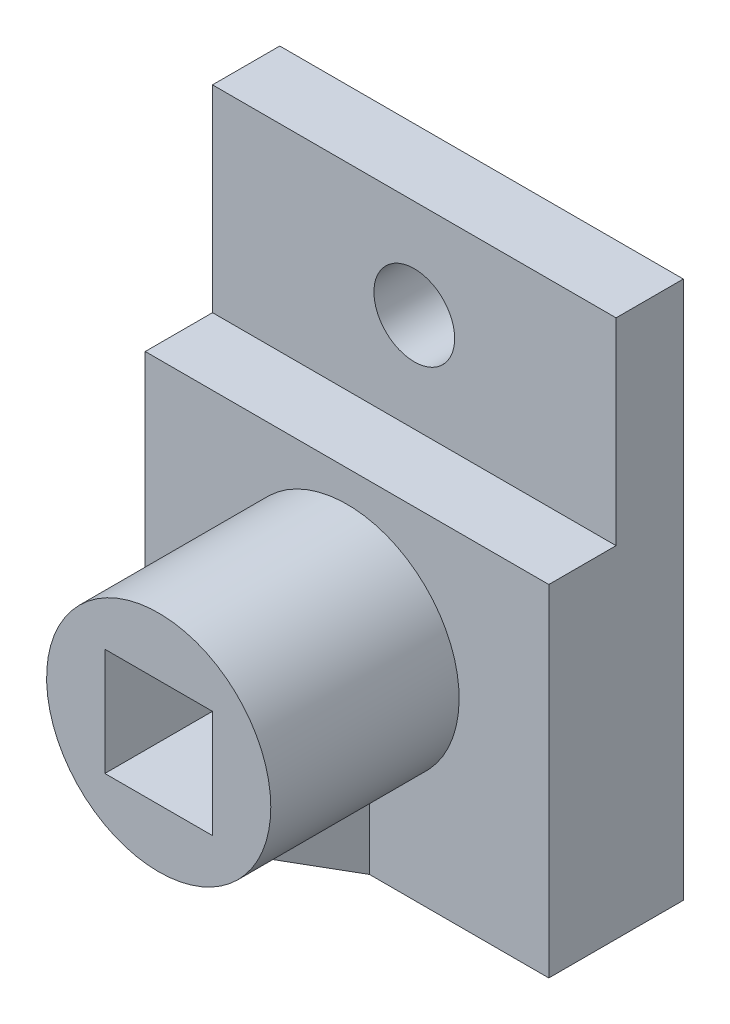
SolidWorks part; units mm, degrees
ref_plane "Спереди" through (0, 0, 0) normal (0, 0, 1) x (1, 0, 0)
ref_plane "Сверху" through (0, 0, 0) normal (0, 1, 0) x (1, 0, 0)
ref_plane "Справа" through (0, 0, 0) normal (1, 0, 0) x (0, 0, -1)
sketch "Эскиз1" plane through (0, 0, 0) normal (0, 0, 1) x (1, 0, 0)
  line L1 (-22.5, -30) -> (22.5, -30)
  line L2 (-22.5, -30) -> (-22.5, 30)
  line L3 (-22.5, 30) -> (22.5, 30)
  line L4 (22.5, -30) -> (22.5, 30)
  line L5 (-22.5, -30) -> (22.5, 30) construction
  line L6 (-22.5, 30) -> (22.5, -30) construction
  point P0 (0, 0)
  dimension "D1" = 45
  dimension "D2" = 60
extrude "Бобышка-Вытянуть1" add sketch "Эскиз1" along normal blind 15
sketch "Эскиз2" plane through (22.5, 0, 0) normal (1, 0, 0) x (0, 0, -1)
  line L0 (-15, 30) -> (0, 30) construction
  line L1 (-15, 30) -> (-7.5, 30)
  line L2 (-15, 30) -> (-15, 8)
  line L3 (-15, 8) -> (-7.5, 8)
  line L4 (-7.5, 30) -> (-7.5, 8)
  dimension "D1" = 22
extrude "Вырез-Вытянуть1" cut sketch "Эскиз2" against normal through all
sketch "Эскиз3" plane through (0, 0, 15) normal (0, 0, 1) x (1, 0, 0)
  line L0 (0, 8) -> (0, -30) construction
  line L1 (-22.5, 8) -> (22.5, 8) construction
  line L2 (-22.5, -30) -> (22.5, -30) construction
  circle A0 centre (0, -8) radius 12.5
  dimension "D1" = 25
  dimension "D2" = 16
extrude "Бобышка-Вытянуть2" add sketch "Эскиз3" along normal blind 21
sketch "Эскиз6" plane through (0, 0, 7.5) normal (0, 0, 1) x (1, 0, 0)
  line L0 (0, 30) -> (0, 8) construction
  line L1 (-22.5, 30) -> (22.5, 30) construction
  line L2 (-22.5, 8) -> (22.5, 8) construction
  circle A0 centre (0, 19) radius 4.5
  dimension "D1" = 9
extrude "Вырез-Вытянуть4" cut sketch "Эскиз6" against normal through all
sketch "Эскиз7" plane through (0, 0, 0) normal (1, 0, 0) x (0, 0, -1)
  line L0 (-30, -20.5) -> (-15, -30)
  line L1 (-36, -20.5) -> (-15, -20.5) construction
  line L2 (-15, -30) -> (-15, 8) construction
  dimension "D1" = 15
rib "Ребро1" sketch "Эскиз7" sketch "Эскиз7" thickness 5 extrusion direction parallel to sketch draft on no parameters "D1"=5
sketch "Эскиз8" plane through (0, 0, 36) normal (0, 0, 1) x (1, 0, 0)
  line L1 (-6, -14) -> (6, -14)
  line L2 (-6, -14) -> (-6, -2)
  line L3 (-6, -2) -> (6, -2)
  line L4 (6, -14) -> (6, -2)
  line L5 (-6, -14) -> (6, -2) construction
  line L6 (-6, -2) -> (6, -14) construction
  point P0 (0, -8)
  point P1 (0, -8)
  dimension "D1" = 12
extrude "Вырез-Вытянуть5" cut sketch "Эскиз8" against normal through all
